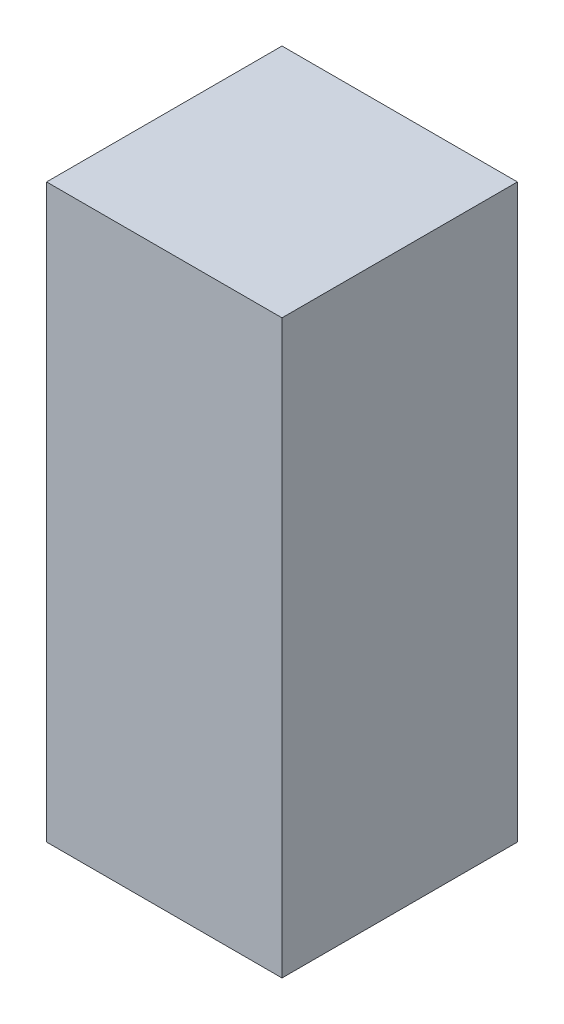
SolidWorks part; units mm, degrees
material "Balsa"
ref_plane "Alzado" through (0, 0, 0) normal (0, 0, 1) x (1, 0, 0)
ref_plane "Planta" through (0, 0, 0) normal (0, 1, 0) x (1, 0, 0)
ref_plane "Vista lateral" through (0, 0, 0) normal (1, 0, 0) x (0, 0, -1)
sketch "Croquis1" plane through (0, 0, 0) normal (0, 1, 0) x (1, 0, 0)
  line L1 (-3.5, -3.5) -> (3.5, -3.5)
  line L2 (-3.5, -3.5) -> (-3.5, 3.5)
  line L3 (-3.5, 3.5) -> (3.5, 3.5)
  line L4 (3.5, -3.5) -> (3.5, 3.5)
  line L5 (-3.5, -3.5) -> (3.5, 3.5) construction
  line L6 (-3.5, 3.5) -> (3.5, -3.5) construction
  point P0 (0, 0)
  dimension "D1" = 7
  dimension "D2" = 7
extrude "Saliente-Extruir1" add sketch "Croquis1" along normal mid plane 17
